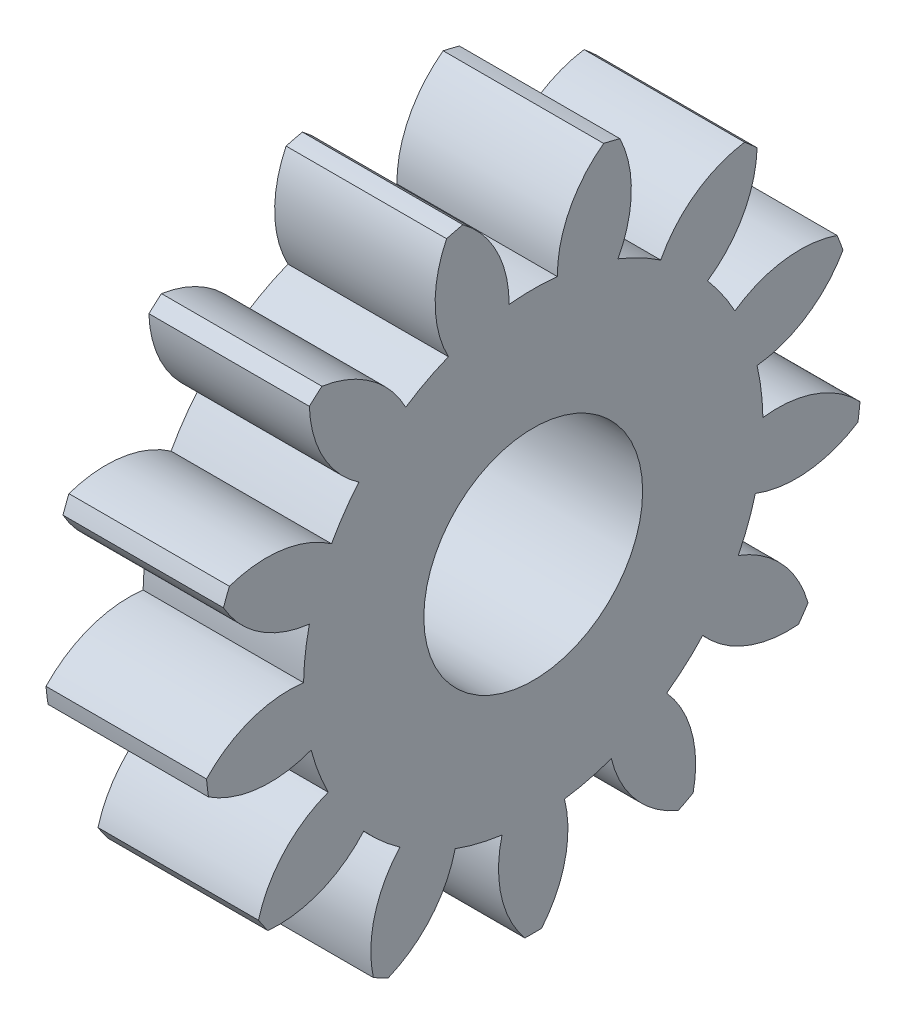
SolidWorks part; units mm, degrees
ref_plane "Plane1" through (0, 0, 0) normal (0, 0, 1) x (1, 0, 0)
ref_plane "Plane2" through (0, 0, 0) normal (0, 1, 0) x (1, 0, 0)
ref_plane "Plane3" through (0, 0, 0) normal (1, 0, 0) x (0, 0, -1)
sketch "HoldingSke" plane through (0, 0, 0) normal (0, 1, 0) x (1, 0, 0)
  line L0 (0, 0) -> (1.624, -0.3749)
  line L1 (-15, 0) -> (100, 0) construction
  line L2 (0, 0) -> (-2.1039, 2.3779)
  line L3 (0, 0) -> (-11.863, 4.5341)
  line L4 (0, 0) -> (8.4147, 1.9427)
  line L5 (0, 0) -> (-46.8476, -17.4728)
  line L6 (0, 0) -> (-1.8237, -1.2305)
  line L7 (-2.1039, 2.3779) -> (8.6586, 51.2059)
  line L8 (-76.2, 54.61) -> (-75.7, 54.61)
  line L9 (-71.009, 38.7566) -> (-53.1078, 45.2721)
  line L10 (-76.2, 71.12) -> (104.1128, 71.12)
  line L11 (0, 0) -> (-2.2, 0)
  line L12 (-76.2, 101.6) -> (-76.177, 101.6)
  line L13 (24.9733, 27.94) -> (52.9518, 28.4284)
  line L14 (24.9733, 27.94) -> (24.9743, 27.94)
  line L15 (24.9733, 27.94) -> (100.4006, 29.5858)
  line L16 (-63.627, -0.6) -> (-12.827, -0.6)
  circle A0 centre (0, 0) radius 1.5
  circle A1 centre (0, 0) radius 3.149
  circle A2 centre (0, 0) radius 37.5
  circle A3 centre (0, 0) radius 1.5
  dimension "MHD" = 6.298
  dimension "Hub_dia" = 75
  dimension "Bore" = 3
  dimension "MBD" = 3
  dimension "Num_teeth" = 13
  dimension "Pitch" = 1.6667
  dimension "Overall_len" = 50
  dimension "Show_teeth" = 13
  dimension "Thickness" = 2.2
  dimension "OAL" = 50.0001
  dimension "T_dim" = 0.5
  dimension "Ap" = 20
  dimension "H" = 19.05
  dimension "Pitch_radius" = 180.3128
  dimension "Width" = 2.2
  dimension "Backlash" = 0.023
  dimension "Addendum_fac" = 1
  dimension "Dedendum_fac" = 1.25
  dimension "Clearance_fac" = 0.25
  dimension "Dedendum_add" = 0.001
  dimension "Module" = 0.6
sketch "BasProSke" plane through (0, 0, 0) normal (0, 1, 0) x (1, 0, 0)
  line L0 (-10, 0) -> (60, 0) construction
  line L1 (0, 0) -> (0, 4.5)
  line L2 (0, 0) -> (2.2, 0)
  line L3 (2.2, 0) -> (2.2, 4.5)
  line L4 (2.2, 4.5) -> (0, 4.5)
  dimension "Thickness" = 2.2
  dimension "Diameter" = 9
revolve "Base-Revolve" add sketch "BasProSke" angle 360 about L0
sketch "TooCutSke" plane through (0, 0, 0) normal (1, 0, 0) x (0, 0, -1)
  line L1 (0, 0) -> (0, 107) construction
  line L2 (0, 0) -> (-0.5103, 3.8665) construction
  line L3 (0, 0) -> (-1.8553, 7.5272) construction
  line L4 (-0.5103, 3.8665) -> (-0.9276, 3.7636) construction
  arc A0 (0.3306, 3.1316) -> (-0.3306, 3.1316) centre (0, 0) ccw
  arc A1 (0.9926, 4.4152) -> (-0.9926, 4.4152) centre (0, 0) ccw
  circle A2 centre (0, 0) radius 3.9 construction
  circle A3 centre (0, 0) radius 3.6648 construction
  arc A4 (-0.3306, 3.1316) -> (-0.9926, 4.4152) centre (-1.8906, 3.1395) ccw
  arc A5 (0.9926, 4.4152) -> (0.3306, 3.1316) centre (1.8906, 3.1395) ccw
  dimension "Root_dia" = 6.298
  dimension "Overcut_dia" = 9.0508
  dimension "Pitch_dia" = 7.8
  dimension "Base_dia" = 7.3296
  dimension "Flank_rad" = 1.56
  dimension "Half_ang" = 13.846
  dimension "Half_CT" = 0.4298
extrude "ToothCut" cut sketch "TooCutSke" along normal through all
fillet "Breaks" [suppressed] radius 0.012
fillet "RootFillets" [suppressed] radius 0.151
pattern_circular "TeethCuts" count 13 every 27.692 about axis through (-10, 0, 0) along (1, 0, 0) of "ToothCut", "RootFillets", "Breaks"
sketch "HubNeaOneSke" plane through (0, 0, 0) normal (-1, 0, 0) x (0, 0, 1)
  circle A0 centre (0, 0) radius 3.149
  dimension "Diameter" = 6.298
extrude "HubNearOne" [suppressed] add sketch "HubNeaOneSke" along normal blind 47.8001
sketch "HubNeaBotSke" plane through (0, 0, 0) normal (-1, 0, 0) x (0, 0, 1)
  circle A0 centre (0, 0) radius 3.149
  dimension "Diameter" = 6.298
extrude "HubNearBoth" [suppressed] add sketch "HubNeaBotSke" along normal blind 23.9
ref_plane "FarPln" through (2.2, 0, 0) normal (1, 0, 0) x (0, 0, -1)
sketch "HubFarSke" plane through (2.2, 0, 0) normal (1, 0, 0) x (0, 0, -1)
  circle A0 centre (0, 0) radius 3.149
  dimension "Diameter" = 6.298
extrude "HubFar" [suppressed] add sketch "HubFarSke" along normal blind 23.9
sketch "BorSke" plane through (0, 0, 0) normal (1, 0, 0) x (0, 0, -1)
  circle A0 centre (0, 0) radius 1.5
  dimension "Diameter" = 3
extrude "Bore" cut sketch "BorSke" along normal mid plane 100.0001
sketch "KeySke" plane through (0, 0, 0) normal (1, 0, 0) x (0, 0, -1)
  line L0 (-0.6, 0) -> (-0.6, 2)
  line L1 (-0.6, 2) -> (0.6, 2)
  line L2 (0.6, 2) -> (0.6, 0)
  line L3 (0, 0) -> (0, 34) construction
  line L4 (-0.6, 0) -> (0.6, 0)
  dimension "Offset" = 2
  dimension "Width" = 1.2
extrude "Keyway" [suppressed] cut sketch "KeySke" along normal mid plane 100.0001
pattern_circular "Keyway2" [suppressed] count 2 every 90 about axis through (-10, 0, 0) along (1, 0, 0)
equation "' \"Module@HoldingSke\" = 6.35"
equation "' \"Num_teeth@HoldingSke\" = 12"
equation "' \"Ap@HoldingSke\" =  20"
equation "' \"Ap@HoldingSke\" = 20"
equation "' \"Width@HoldingSke\" = 0.5 * 25.4"
equation "' \"Hub_dia@HoldingSke\"= 1 * 25.4"
equation "' \"Hub_dia@HoldingSke\" = 1 * 25.4"
equation "' \"Overall_len@HoldingSke\" = 1.0 * 25.4"
equation "' \"Bore@HoldingSke\" = 0.75 * 25.4"
equation "' \"T_dim@HoldingSke\" = 0.1 * 25.4"
equation "' \"Width@KeySke\" = 0.25 * 25.4"
equation "' \"Show_teeth@HoldingSke\" = 13"
equation "' \"Backlash@HoldingSke\" = 0.009 * 25.4"
equation "' \"Addendum_fac@HoldingSke\" = 1.0"
equation "' \"Dedendum_fac@HoldingSke\" = 1.25"
equation "' \"Dedendum_add@HoldingSke\" = 0.00005 * 25.4"
equation "' \"Clearance_fac@HoldingSke\" = 0.25"
equation "\"Pitch@HoldingSke\" = 1 / \"Module@HoldingSke\""
equation "\"Overcut_dia@TooCutSke\" = (\"Num_teeth@HoldingSke\" + 2 * \"Addendum_fac@HoldingSke\") / \"Pitch@HoldingSke\" + 0.002 * 25.4"
equation "\"Pitch_dia@TooCutSke\" = \"Num_teeth@HoldingSke\" / \"Pitch@HoldingSke\""
equation "\"Base_dia@TooCutSke\" = \"Num_teeth@HoldingSke\" / \"Pitch@HoldingSke\" * cos((\"Ap@HoldingSke\"  * 3.14159265 / 180))"
equation "\"Root_dia@TooCutSke\" = (\"Num_teeth@HoldingSke\" + 2) / \"Pitch@HoldingSke\" - 2 * (\"Addendum_fac@HoldingSke\" + \"Dedendum_fac@HoldingSke\") / \"Pitch@HoldingSke\" - \"Dedendum_add@HoldingSke\" * 2"
equation "\"Half_ang@TooCutSke\" = 180 / \"Num_teeth@HoldingSke\""
equation "\"Half_CT@TooCutSke\" = \"Num_teeth@HoldingSke\" / \"Pitch@HoldingSke\" * sin((3.14159265 / 2 / \"Num_teeth@HoldingSke\")) / 2 - 7 * \"Backlash@HoldingSke\" / 4"
equation "\"Flank_rad@TooCutSke\" = \"Num_teeth@HoldingSke\" / \"Pitch@HoldingSke\" / 5"
equation "\"Radius@RootFillets\" = \"Clearance_fac@HoldingSke\" / \"Pitch@HoldingSke\" + \"Dedendum_add@HoldingSke\""
equation "\"Break_rad@Breaks\" = 0.02 / \"Pitch@HoldingSke\""
equation "\"Thickness@HoldingSke\" = \"Width@HoldingSke\""
equation "\"OAL@HoldingSke\" = \"Thickness@HoldingSke\""
equation "\"MHD@HoldingSke\" = (\"Num_teeth@HoldingSke\" + 2) / \"Pitch@HoldingSke\" - 2 * (\"Addendum_fac@HoldingSke\" + \"Dedendum_fac@HoldingSke\")  / \"Pitch@HoldingSke\" - \"Dedendum_add@HoldingSke\" * 2"
equation "\"MBD@HoldingSke\" = (\"Num_teeth@HoldingSke\" + 2) / \"Pitch@HoldingSke\" - 2 * (\"Addendum_fac@HoldingSke\" + \"Dedendum_fac@HoldingSke\")  / \"Pitch@HoldingSke\" - \"Dedendum_add@HoldingSke\" * 2 - 0.002 * 25.4"
equation "\"MHD@HoldingSke\" = ((sgn( \"MHD@HoldingSke\" - \"Hub_dia@HoldingSke\" )-1)*( \"MHD@HoldingSke\" - \"Hub_dia@HoldingSke\" ))/-2+ \"Hub_dia@HoldingSke\""
equation "\"MBD@HoldingSke\" = ((sgn( \"MBD@HoldingSke\" - \"Bore@HoldingSke\" )-1)*( \"MBD@HoldingSke\" - \"Bore@HoldingSke\" ))/-2+ \"Bore@HoldingSke\""
equation "\"OAL@HoldingSke\" = ((sgn( \"OAL@HoldingSke\" - \"Overall_len@HoldingSke\" )+1)*( \"OAL@HoldingSke\" - \"Overall_len@HoldingSke\" ))/2 + \"Overall_len@HoldingSke\" + 0.000002 * 25.4"
equation "\"Num_teeth@TeethCuts\" = int( \"Show_teeth@HoldingSke\" ) + 1"
equation "\"Num_teeth@TeethCuts\" = ((sgn( \"Num_teeth@TeethCuts\" - \"Num_teeth@HoldingSke\" )-1)*( \"Num_teeth@TeethCuts\" - \"Num_teeth@HoldingSke\" ))/-2+ \"Num_teeth@HoldingSke\""
equation "\"Num_teeth@TeethCuts\" = ((sgn( \"Num_teeth@TeethCuts\" - 2.0)+1)*( \"Num_teeth@TeethCuts\" - 2.0))/2 +2.0"
equation "\"Angle@TeethCuts\" = 360.0 / \"Num_teeth@HoldingSke\""
equation "\"Diameter@BasProSke\" = (\"Num_teeth@HoldingSke\" + 2 * \"Addendum_fac@HoldingSke\") / \"Pitch@HoldingSke\""
equation "\"Thickness@BasProSke\"  = \"Thickness@HoldingSke\""
equation "' \"Fillet_rad@BasProSke\" =  \"Thickness@HoldingSke\" * 0.05"
equation "' \"Fillet_rad@BasProSke\" = \"Thickness@HoldingSke\" * 0.05"
equation "\"MHD@HoldingSke\" = ((sgn( \"MHD@HoldingSke\" - \"Root_dia@TooCutSke\" )-1)*( \"MHD@HoldingSke\" - \"Root_dia@TooCutSke\" ))/-2+ \"Root_dia@TooCutSke\""
equation "\"Diameter@HubNeaOneSke\" = \"MHD@HoldingSke\""
equation "\"Length@HubNearOne\" = \"OAL@HoldingSke\" - \"Thickness@BasProSke\""
equation "\"Diameter@HubNeaBotSke\" = \"MHD@HoldingSke\""
equation "\"Length@HubNearBoth\" = ( \"OAL@HoldingSke\" - \"Thickness@BasProSke\" ) / 2.0"
equation "\"Thickness@FarPln\" = \"Thickness@BasProSke\""
equation "\"Diameter@HubFarSke\" = \"MHD@HoldingSke\""
equation "\"Length@HubFar\" = ( \"OAL@HoldingSke\" - \"Thickness@BasProSke\" ) / 2.0"
equation "\"Diameter@BorSke\" = \"MBD@HoldingSke\""
equation "\"D1@Bore\" = \"OAL@HoldingSke\" * 2.0"
equation "\"D1@Keyway\" = \"OAL@HoldingSke\" * 2.0"
equation "\"Offset@KeySke\" = \"T_dim@HoldingSke\" + \"MBD@HoldingSke\" / 2.0"
